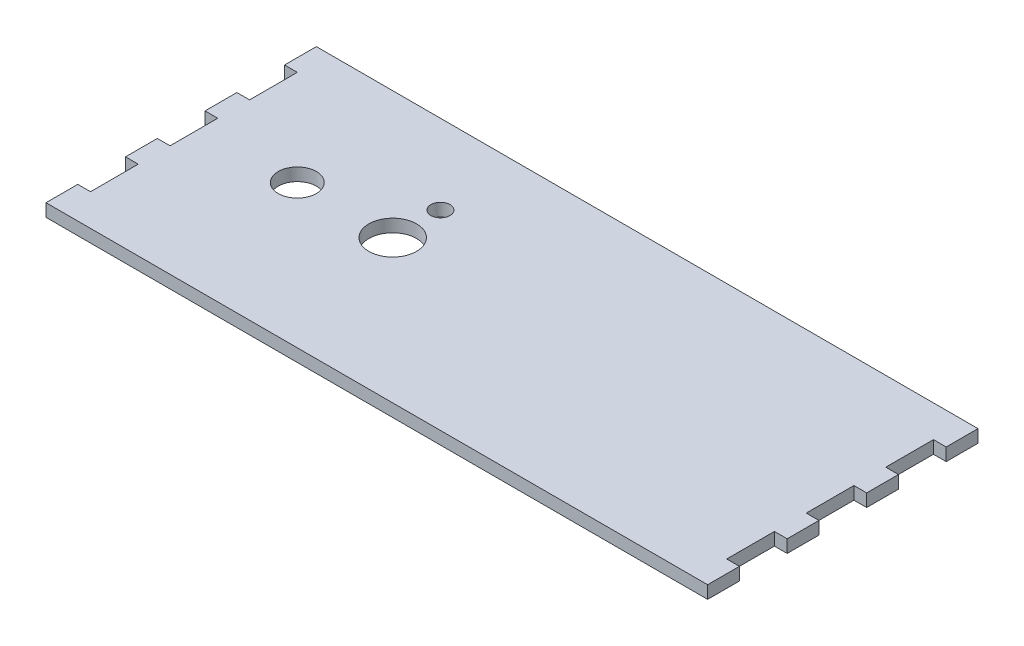
SolidWorks part; units mm, degrees
ref_plane "Front Plane" through (0, 0, 0) normal (0, 0, 1) x (1, 0, 0)
ref_plane "Top Plane" through (0, 0, 0) normal (0, 1, 0) x (1, 0, 0)
ref_plane "Right Plane" through (0, 0, 0) normal (1, 0, 0) x (0, 0, -1)
sketch "Sketch1" plane through (0, 0, 0) normal (0, 1, 0) x (1, 0, 0)
  line L1 (0, 0) -> (200, 0)
  line L2 (0, 0) -> (0, 85)
  line L3 (0, 85) -> (200, 85)
  line L4 (200, 0) -> (200, 85)
  line L5 (0, 0) -> (-4, 0)
  line L6 (0, 0) -> (0, 10)
  line L7 (0, 10) -> (-4, 10)
  line L8 (-4, 0) -> (-4, 10)
  line L9 (0, 85) -> (-4, 85)
  line L10 (0, 85) -> (0, 75)
  line L11 (0, 75) -> (-4, 75)
  line L12 (-4, 85) -> (-4, 75)
  line L13 (0, 25) -> (-4, 25)
  line L14 (0, 25) -> (0, 35)
  line L15 (0, 35) -> (-4, 35)
  line L16 (-4, 25) -> (-4, 35)
  line L17 (0, 60) -> (-4, 60)
  line L18 (0, 60) -> (0, 50)
  line L19 (0, 50) -> (-4, 50)
  line L20 (-4, 60) -> (-4, 50)
  line L21 (200, 0) -> (204, 0)
  line L22 (200, 0) -> (200, 10)
  line L23 (200, 10) -> (204, 10)
  line L24 (204, 0) -> (204, 10)
  line L25 (200, 25) -> (204, 25)
  line L26 (200, 25) -> (200, 35)
  line L27 (200, 35) -> (204, 35)
  line L28 (204, 25) -> (204, 35)
  line L29 (200, 50) -> (204, 50)
  line L30 (200, 50) -> (200, 60)
  line L31 (200, 60) -> (204, 60)
  line L32 (204, 50) -> (204, 60)
  line L33 (200, 85) -> (204, 85)
  line L34 (200, 85) -> (200, 75)
  line L35 (200, 75) -> (204, 75)
  line L36 (204, 85) -> (204, 75)
  circle A0 centre (30, 45) radius 6
  circle A1 centre (60, 45) radius 7.5
  circle A2 centre (60, 60) radius 3
  dimension "D19" = 12
  dimension "D20" = 30
  dimension "D21" = 40
  dimension "D22" = 15
  dimension "D23" = 30
  dimension "D24" = 6
  dimension "D25" = 15
  dimension "D1" = 200
  dimension "D3" = 10
  dimension "D4" = 10
  dimension "D5" = 10
  dimension "D6" = 10
  dimension "D7" = 4
  dimension "D8" = 4
  dimension "D9" = 4
  dimension "D10" = 4
  dimension "D11" = 15
  dimension "D12" = 15
  dimension "D13" = 15
  dimension "D14" = 15
  dimension "D15" = 15
  dimension "D16" = 10
  dimension "D17" = 15
  dimension "D18" = 4
  dimension "D26" = 10
  dimension "D27" = 10
  dimension "D28" = 10
  dimension "D29" = 85
extrude "Boss-Extrude4" add sketch "Sketch1" along normal blind 4
